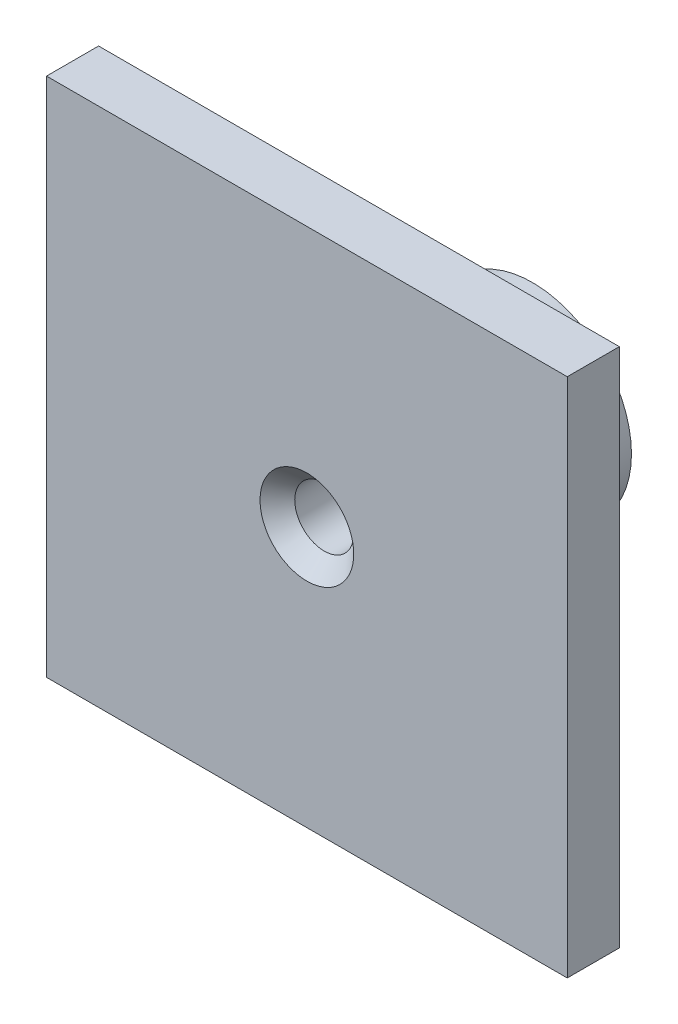
SolidWorks part; units mm, degrees
material "Сосна"
ref_plane "Front" through (0, 0, 0) normal (0, 0, 1) x (1, 0, 0)
ref_plane "Top" through (0, 0, 0) normal (0, 1, 0) x (1, 0, 0)
ref_plane "Right" through (0, 0, 0) normal (1, 0, 0) x (0, 0, -1)
sketch "Эскиз2" plane through (0, 0, 0) normal (0, 0, 1) x (1, 0, 0)
  line L1 (-7.5, -7.5) -> (7.5, -7.5)
  line L2 (-7.5, -7.5) -> (-7.5, 7.5)
  line L3 (-7.5, 7.5) -> (7.5, 7.5)
  line L4 (7.5, -7.5) -> (7.5, 7.5)
  line L5 (-7.5, -7.5) -> (7.5, 7.5) construction
  line L6 (-7.5, 7.5) -> (7.5, -7.5) construction
  point P0 (0, 0)
  dimension "D1" = 15
extrude "Основание" add sketch "Эскиз2" along normal blind 1.5
sketch "Эскиз3" plane through (0, 0, 0) normal (0, 0, 1) x (1, 0, 0)
  circle A0 centre (0, 0) radius 0.85
  circle A1 centre (0, 0) radius 2.85
  dimension "D1" = 1.7
  dimension "D2" = 2
  dimension "D3" = 5.7
extrude "Стойка" add sketch "Эскиз3" against normal blind 5
chamfer "Фаска1" distance 2 angle 45 1 edges at (2.85, 0, 0)
sketch "Эскиз5" plane through (0, 0, 0) normal (0, 0, 1) x (1, 0, 0)
  circle A0 centre (0, 0) radius 0.85
  circle A1 centre (0, 0) radius 0.85 construction
extrude "Вырез-Вытянуть2" cut sketch "Эскиз5" along normal through all
chamfer "Фаска3" distance 0.5 angle 45 1 edges at (0.85, 0, 1.5)
